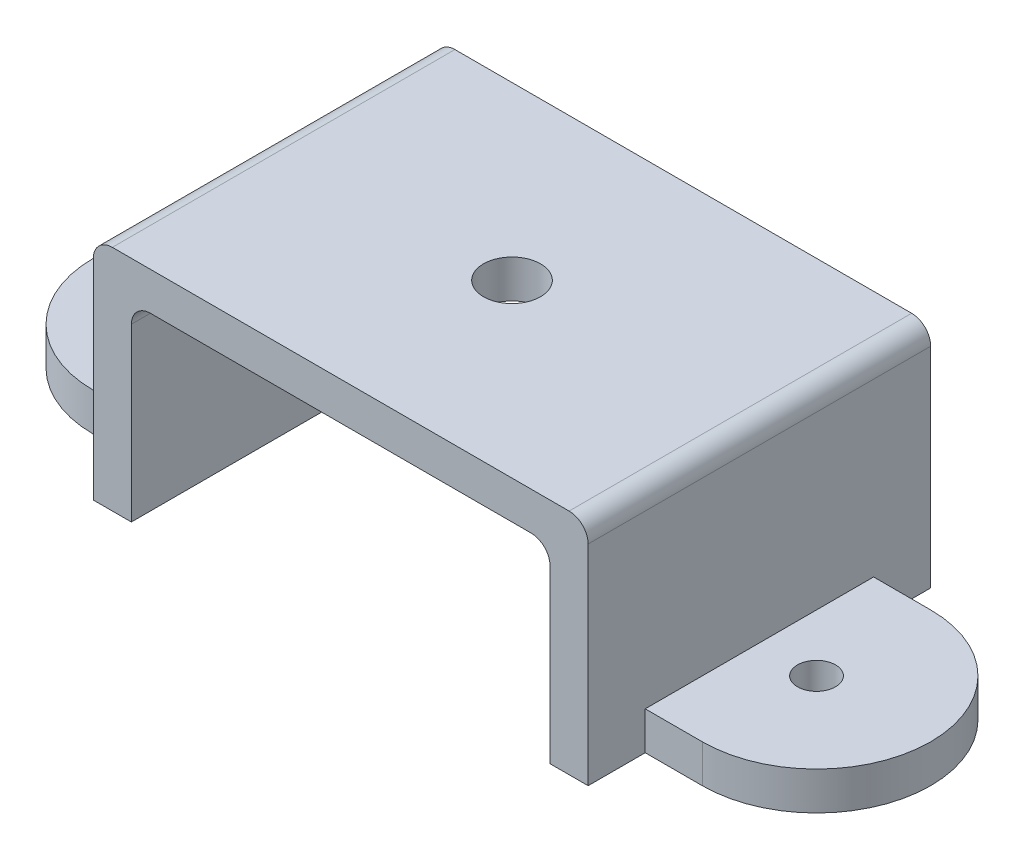
SolidWorks part; units mm, degrees
ref_plane "Front Plane" through (0, 0, 0) normal (0, 0, 1) x (1, 0, 0)
ref_plane "Top Plane" through (0, 0, 0) normal (0, 1, 0) x (1, 0, 0)
ref_plane "Right Plane" through (0, 0, 0) normal (1, 0, 0) x (0, 0, -1)
sketch "Sketch1" plane through (0, 0, 0) normal (0, 1, 0) x (1, 0, 0)
  line L1 (-101.6, 38.1) -> (101.6, 38.1)
  line L2 (-101.6, 38.1) -> (-101.6, -38.1)
  line L3 (-101.6, -38.1) -> (101.6, -38.1)
  line L4 (101.6, 38.1) -> (101.6, -38.1)
  circle A0 centre (-101.6, 0) radius 38.1
  circle A1 centre (101.6, 0) radius 38.1
  dimension "D1" = 76.2
  dimension "D2" = 203.2
  dimension "D3" = 101.6
  dimension "D4" = 38.1
extrude "Boss-Extrude1" add sketch "Sketch1" along normal blind 12.7 contours A1 L1 A0 L3 | L2 A0 | L2 A0 | L4 A1 | L4 A1
sketch "Sketch2" plane through (0, 0, 0) normal (0, 0, 1) x (1, 0, 0)
  line L0 (-101.6, 0) -> (101.6, 0) construction
  line L1 (-82.55, 0) -> (-69.85, 0)
  line L2 (69.85, 0) -> (82.55, 0)
  line L4 (-82.55, 0) -> (82.55, 0)
  line L5 (-82.55, 0) -> (-82.55, 76.2)
  line L6 (-82.55, 76.2) -> (82.55, 76.2)
  line L7 (82.55, 0) -> (82.55, 76.2)
  line L8 (-69.85, 0) -> (69.85, 0)
  line L9 (-69.85, 0) -> (-69.85, 63.5)
  line L10 (-69.85, 63.5) -> (69.85, 63.5)
  line L11 (69.85, 0) -> (69.85, 63.5)
  dimension "D1" = 165.1
  dimension "D2" = 139.7
  dimension "D3" = 12.7
  dimension "D4" = 76.2
  dimension "D5" = 12.7
  dimension "D6" = 69.85
extrude "Boss-Extrude2" add sketch "Sketch2" along normal blind 57.15 and the other way blind 57.15 contours L11 L2 L7 L6 L5 L1 L9 L10
sketch "Sketch8" plane through (0, 0, 0) normal (0, 1, 0) x (1, 0, 0)
  circle A0 centre (0, 0) radius 9.525
  dimension "D1" = 19.05
extrude "Cut-Extrude2" cut sketch "Sketch8" along normal through all
sketch "Sketch9" plane through (0, 0, 57.15) normal (0, 0, 1) x (1, 0, 0)
  line L0 (-69.85, 0) -> (69.85, 0)
  line L1 (69.85, 0) -> (69.85, 63.5)
  line L2 (69.85, 63.5) -> (-69.85, 63.5)
  line L3 (-69.85, 63.5) -> (-69.85, 0)
extrude "Cut-Extrude3" cut sketch "Sketch9" against normal through all
fillet "Fillet1" radius 6.35 4 edges at (-69.85, 63.5, 0) (69.85, 63.5, 0) (82.55, 76.2, 0) (-82.55, 76.2, 0)
sketch "Sketch10" plane through (0, 12.7, 0) normal (0, 1, 0) x (1, 0, 0)
  circle A0 centre (101.6, 0) radius 6.35
  circle A1 centre (-101.6, 0) radius 6.35
  arc A2 (-101.6, 38.1) -> (-101.6, -38.1) centre (-101.6, 0) ccw construction
  arc A3 (101.6, -38.1) -> (101.6, 38.1) centre (101.6, 0) ccw construction
  dimension "D1" = 12.7
extrude "Cut-Extrude4" cut sketch "Sketch10" against normal through all
